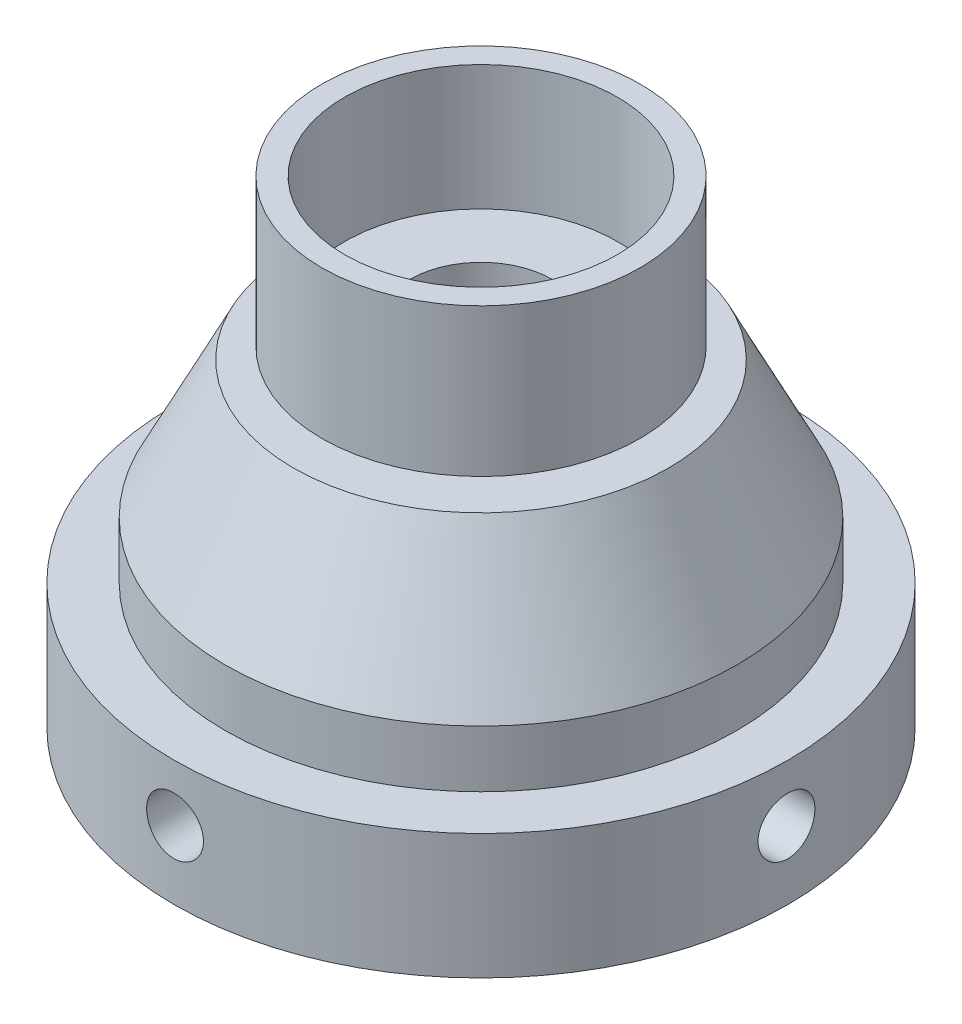
SolidWorks part; units mm, degrees
material "Gray Cast Iron"
ref_plane "Front Plane" through (0, 0, 0) normal (0, 0, 1) x (1, 0, 0)
ref_plane "Top Plane" through (0, 0, 0) normal (0, 1, 0) x (1, 0, 0)
ref_plane "Right Plane" through (0, 0, 0) normal (1, 0, 0) x (0, 0, -1)
sketch "Sketch1" plane through (0, 0, 0) normal (0, 0, 1) x (1, 0, 0)
  line L0 (0, 70.9983) -> (0, -26.3708) construction
  line L1 (24, 84) -> (24, 62)
  line L2 (24, 62) -> (12.5, 62)
  line L3 (12.5, 62) -> (12.5, 6)
  line L4 (12.5, 6) -> (31, 6)
  line L5 (31, 6) -> (31, 0)
  line L6 (31, 0) -> (54, 0)
  line L7 (54, 0) -> (54, 22)
  line L8 (54, 22) -> (45, 22)
  line L9 (45, 22) -> (45, 32)
  line L10 (45, 32) -> (33, 56)
  line L11 (33, 56) -> (25.1429, 56)
  line L12 (25.1429, 56) -> (25.1429, 58)
  line L13 (25.1429, 58) -> (28, 58)
  line L14 (28, 58) -> (28, 84)
  line L15 (28, 84) -> (24, 84)
  dimension "D1" = 22
  dimension "D2" = 6
  dimension "D3" = 54
  dimension "D4" = 31
  dimension "D5" = 12.5
  dimension "D6" = 24
  dimension "D7" = 28
  dimension "D8" = 2
  dimension "D9" = 24
  dimension "D10" = 33
  dimension "D11" = 26
  dimension "D12" = 22
  dimension "D13" = 10
  dimension "D14" = 45
revolve "Revolve1" add sketch "Sketch1" angle 360 about L0
cosmetic thread "Cosmetic Thread1" parameters "D2"=51.61
sketch "Sketch2" plane through (0, 62, 0) normal (0, 1, 0) x (1, 0, 0)
  line L1 (10.5989, 2.5) -> (14.5, 2.5)
  line L2 (10.5989, 2.5) -> (10.5989, -2.5)
  line L3 (10.5989, -2.5) -> (14.5, -2.5)
  line L4 (14.5, 2.5) -> (14.5, -2.5)
  dimension "D1" = 5
  dimension "D2" = 2.5
  dimension "D3" = 14.5
extrude "Cut-Extrude1" cut sketch "Sketch2" against normal through all
hole_wizard "Ø10.0 (10) Diameter Hole1" positions "3DSketch3" profile "Sketch10" hole size "Ø10.0" standard "ISO"
sketch3d "3DSketch3"
  point P0 (-0.0443, 12, 54)
  dimension "D1" = 12
sketch "Sketch10" plane through (-0.0443, 12, 54) normal (0, 1, 0) x (1, 0, 0.0008)
  line L0 (0, 0) -> (0, 13.0043)
  line L1 (0, 13.0043) -> (5, 10)
  line L2 (5, 10) -> (5, 0)
  line L5 (5, 0) -> (0, 0)
  line L10 (0, 13.0043) -> (-5, 10) construction
  line L11 (0, -6.35) -> (0, 107.95) construction
  dimension "Hole Dia." = 10
  dimension "Hole Depth" = 10
  dimension "Drill Angle" = 118
pattern_circular "CirPattern1" count 4 over 360 about axis through (0, 0, 0) along (0, 1, 0) of "Ø10.0 (10) Diameter Hole1"
